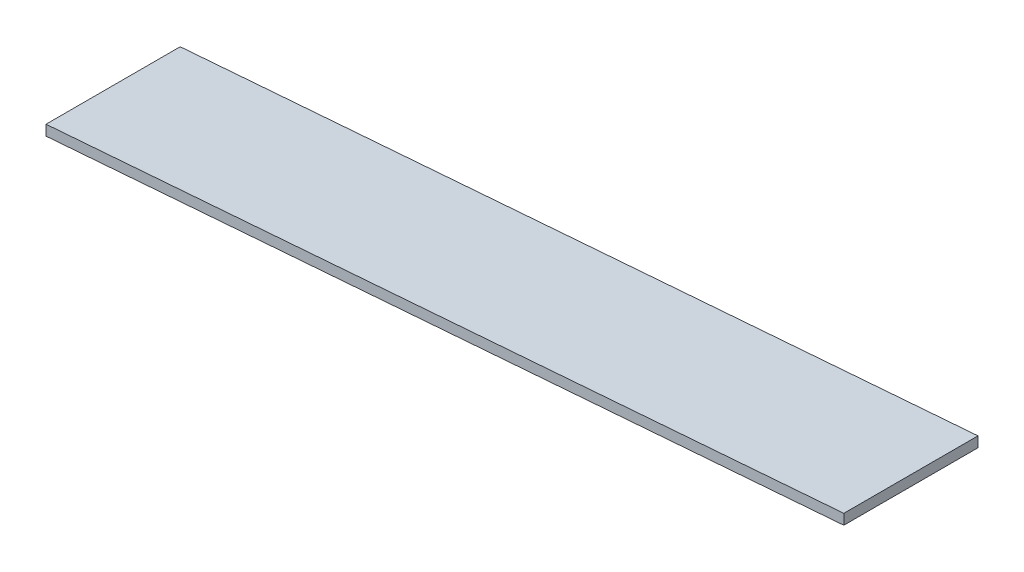
SolidWorks part; units mm, degrees
ref_plane "前基準面" through (0, 0, 0) normal (0, 0, 1) x (1, 0, 0)
ref_plane "上基準面" through (0, 0, 0) normal (0, 1, 0) x (1, 0, 0)
ref_plane "右基準面" through (0, 0, 0) normal (1, 0, 0) x (0, 0, -1)
sketch "草圖1" plane through (0, 0, 0) normal (0, 0, 1) x (1, 0, 0)
  line L0 (0, 0) -> (77.3, 6.0022)
  line L1 (0, 0) -> (172.4771, 0) construction
  line L2 (0, 0) -> (0, 1.003)
  line L3 (0, 1.003) -> (77.3, 7.0052)
  line L4 (77.3, 6.0022) -> (77.3, 7.0052)
  dimension "D1" = 4.44
  dimension "D2" = 77.3
  dimension "D3" = 1
extrude "填料-伸長1" add sketch "草圖1" along normal mid plane 13 contours L3 L4 L0 L2
